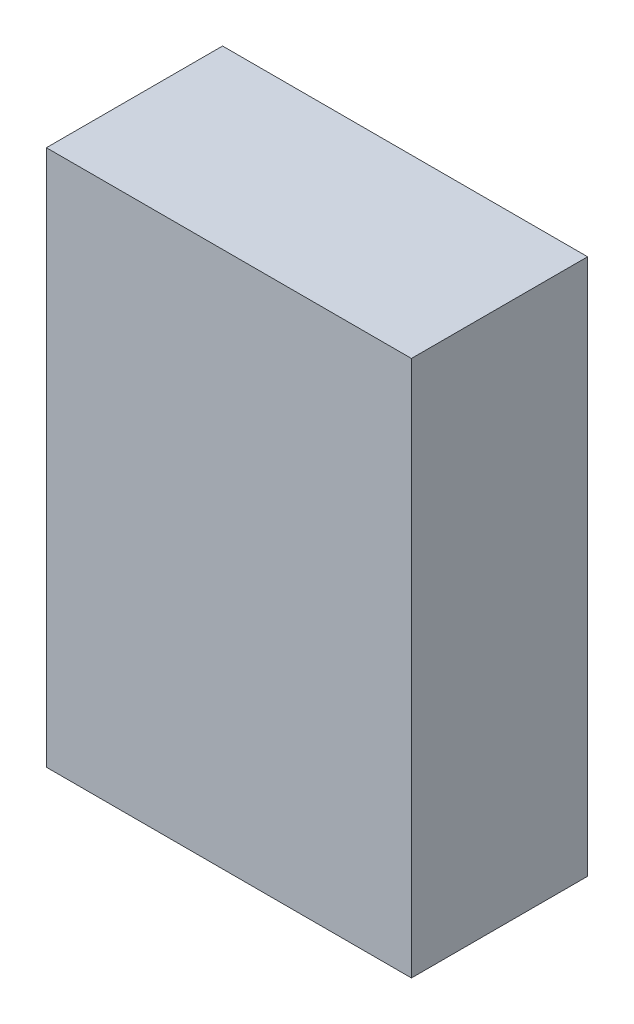
SolidWorks part; units mm, degrees
ref_plane "Front Plane" through (0, 0, 0) normal (0, 0, 1) x (1, 0, 0)
ref_plane "Top Plane" through (0, 0, 0) normal (0, 1, 0) x (1, 0, 0)
ref_plane "Right Plane" through (0, 0, 0) normal (1, 0, 0) x (0, 0, -1)
sketch "Sketch1" plane through (0, 0, 0) normal (0, 0, 1) x (1, 0, 0)
  line L1 (-13.78, -20.255) -> (13.78, -20.255)
  line L2 (-13.78, -20.255) -> (-13.78, 20.255)
  line L3 (-13.78, 20.255) -> (13.78, 20.255)
  line L4 (13.78, -20.255) -> (13.78, 20.255)
  line L5 (-13.78, -20.255) -> (13.78, 20.255) construction
  line L6 (-13.78, 20.255) -> (13.78, -20.255) construction
  point P0 (0, 0)
extrude "Envelope" add sketch "Sketch1" along normal blind 13.3
